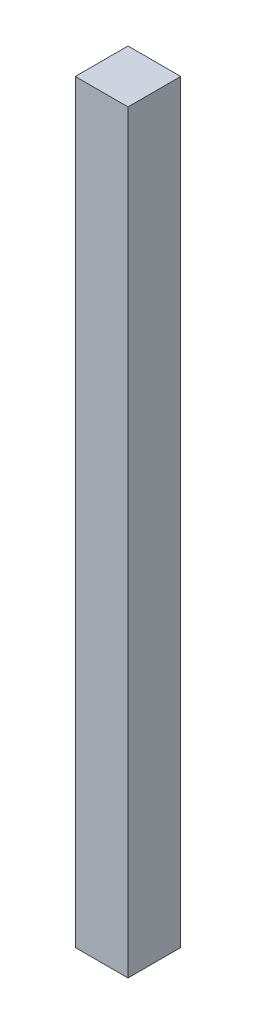
SolidWorks part; units mm, degrees
ref_plane "Front Plane" through (0, 0, 0) normal (0, 0, 1) x (1, 0, 0)
ref_plane "Top Plane" through (0, 0, 0) normal (0, 1, 0) x (1, 0, 0)
ref_plane "Right Plane" through (0, 0, 0) normal (1, 0, 0) x (0, 0, -1)
sketch "Sketch1" plane through (0, 0, 0) normal (0, 1, 0) x (1, 0, 0)
  line L1 (-5.244, 5.244) -> (5.244, 5.244)
  line L2 (-5.244, 5.244) -> (-5.244, -5.244)
  line L3 (-5.244, -5.244) -> (5.244, -5.244)
  line L4 (5.244, 5.244) -> (5.244, -5.244)
  line L5 (-5.244, 5.244) -> (5.244, -5.244) construction
  line L6 (-5.244, -5.244) -> (5.244, 5.244) construction
  point P0 (0, 0)
  dimension "D1" = 10.4881
  dimension "D2" = 10.4881
extrude "Boss-Extrude1" add sketch "Sketch1" along normal blind 150
